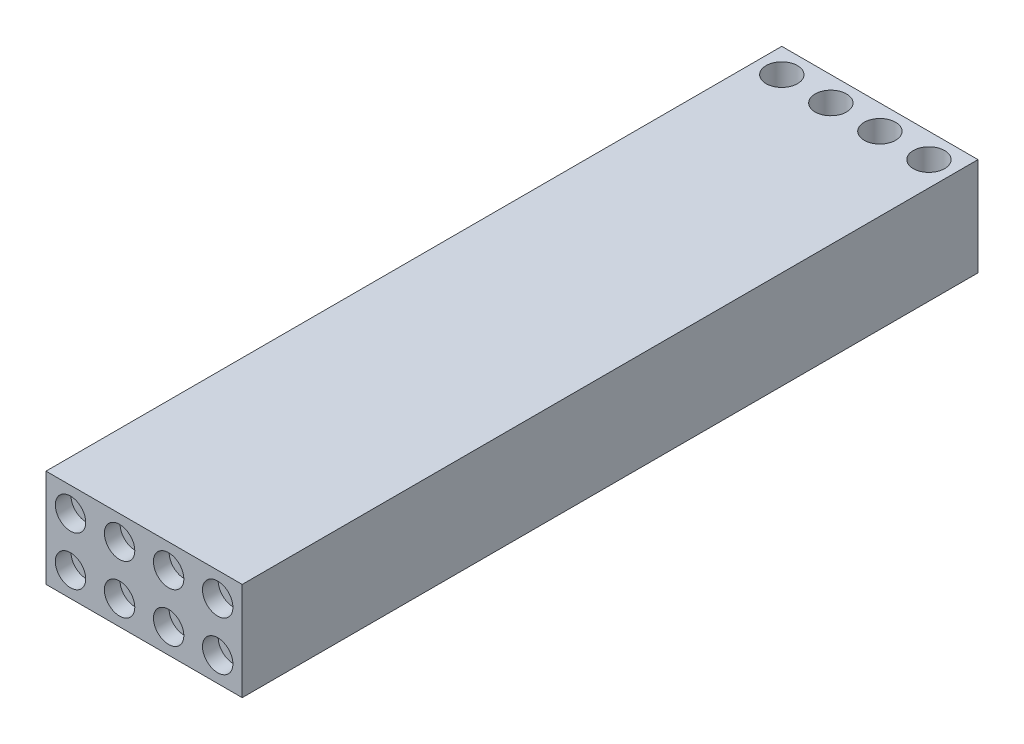
SolidWorks part; units mm, degrees
ref_plane "正面" through (0, 0, 0) normal (0, 0, 1) x (1, 0, 0)
ref_plane "平面" through (0, 0, 0) normal (0, 1, 0) x (1, 0, 0)
ref_plane "右側面" through (0, 0, 0) normal (1, 0, 0) x (0, 0, -1)
sketch "ｽｹｯﾁ1" plane through (0, 0, 0) normal (0, 0, 1) x (1, 0, 0)
  line L1 (-10, 10) -> (10, 10)
  line L2 (-10, 10) -> (-10, -10)
  line L3 (-10, -10) -> (10, -10)
  line L4 (10, 10) -> (10, -10)
  line L5 (-10, 10) -> (10, -10) construction
  line L6 (-10, -10) -> (10, 10) construction
  point P0 (0, 0)
  dimension "D1" = 20
  dimension "D2" = 20
extrude "ﾎﾞｽ - 押し出し1" add sketch "ｽｹｯﾁ1" along normal blind 150
sketch "ｽｹｯﾁ3" plane through (0, 10, 0) normal (0, 1, 0) x (1, 0, 0)
  line L0 (10, 0) -> (-10, 0) construction
  line L1 (10, -150) -> (10, 0) construction
  circle A0 centre (5, -5) radius 3.2
  dimension "D1" = 6.4
  dimension "D2" = 5
  dimension "D3" = 5
extrude "ｶｯﾄ - 押し出し2" cut sketch "ｽｹｯﾁ3" against normal blind 18
mirror "ﾐﾗｰ1" about plane through (0, 0, 0) normal (1, 0, 0) of "ｶｯﾄ - 押し出し2"
sketch "ｽｹｯﾁ4" plane through (0, 0, 150) normal (0, 0, 1) x (1, 0, 0)
  line L0 (10, -10) -> (10, 10) construction
  line L1 (10, 10) -> (-10, 10) construction
  circle A0 centre (5, 5) radius 3.1
  dimension "D1" = 6.2
  dimension "D2" = 5
  dimension "D3" = 5
extrude "ｶｯﾄ - 押し出し3" cut sketch "ｽｹｯﾁ4" against normal blind 3.2
mirror "ﾐﾗｰ2" about plane through (0, 0, 0) normal (0, 1, 0) of "ｶｯﾄ - 押し出し3"
mirror "ﾐﾗｰ3" about plane through (0, 0, 0) normal (1, 0, 0) of "ﾐﾗｰ2", "ｶｯﾄ - 押し出し3"
mirror "ﾐﾗｰ4" about plane through (-10, 10, 150) normal (1, 0, 0) of "ﾐﾗｰ1", "ﾐﾗｰ3", "ﾎﾞｽ - 押し出し1", "ｶｯﾄ - 押し出し2", "ｶｯﾄ - 押し出し3", "ﾐﾗｰ2"
